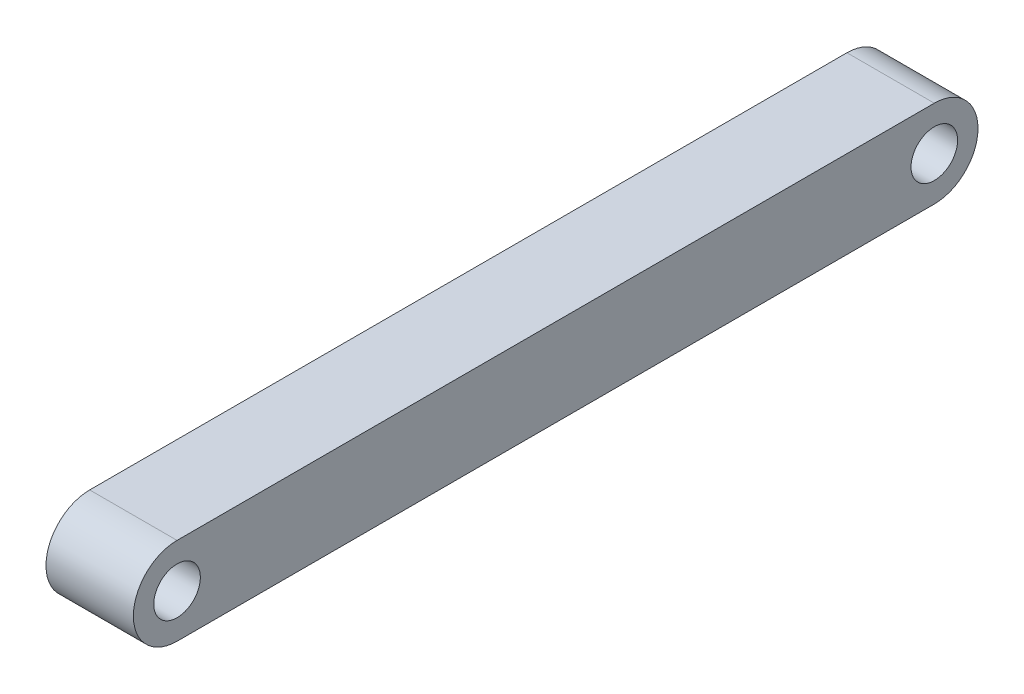
SolidWorks part; units mm, degrees
ref_plane "Front Plane" through (0, 0, 0) normal (0, 0, 1) x (1, 0, 0)
ref_plane "Top Plane" through (0, 0, 0) normal (0, 1, 0) x (1, 0, 0)
ref_plane "Right Plane" through (0, 0, 0) normal (1, 0, 0) x (0, 0, -1)
sketch "Sketch1" plane through (0, 0, 0) normal (1, 0, 0) x (0, 0, -1)
  line L0 (-65, 0) -> (65, 0) construction
  line L1 (-65, 7.5) -> (65, 7.5)
  line L2 (-65, -7.5) -> (65, -7.5)
  arc A0 (-65, 7.5) -> (-65, -7.5) centre (-65, 0) ccw
  arc A1 (65, -7.5) -> (65, 7.5) centre (65, 0) ccw
  circle A2 centre (-65, 0) radius 4
  circle A3 centre (65, 0) radius 4
  point P2 (0, 0)
  dimension "D1" = 8
  dimension "D2" = 8
  dimension "D3" = 15
  dimension "D4" = 130
extrude "Boss-Extrude1" add sketch "Sketch1" along normal mid plane 15
